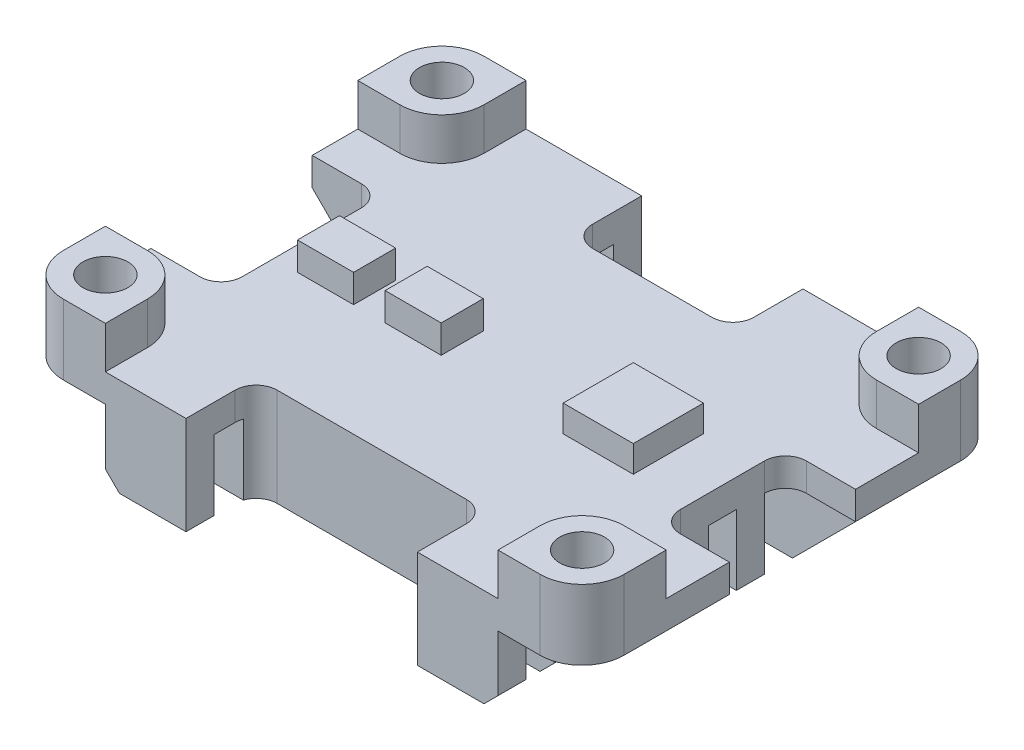
SolidWorks part; units mm, degrees
material "1060 Сплав"
ref_plane "Спереди" through (0, 0, 0) normal (0, 0, 1) x (1, 0, 0)
ref_plane "Сверху" through (0, 0, 0) normal (0, 1, 0) x (1, 0, 0)
ref_plane "Справа" through (0, 0, 0) normal (1, 0, 0) x (0, 0, -1)
other "Configuration Table"
sketch "Эскиз1" plane through (0, 0, 0) normal (0, 1, 0) x (1, 0, 0)
  line L1 (-17, 15) -> (17, 15)
  line L2 (-20, 12) -> (-20, -12)
  line L3 (-17, -15) -> (17, -15)
  line L4 (20, 12) -> (20, -12)
  line L5 (-20, 15) -> (20, -15) construction
  line L6 (-20, -15) -> (20, 15) construction
  line L7 (-17, -12) -> (17, -12) construction
  line L8 (-17, -12) -> (-17, 12) construction
  line L9 (-17, 12) -> (17, 12) construction
  line L10 (17, -12) -> (17, 12) construction
  line L11 (-17, -12) -> (17, 12) construction
  line L12 (-17, 12) -> (17, -12) construction
  arc A0 (-20, -12) -> (-17, -15) centre (-17, -12) ccw
  arc A1 (17, -15) -> (20, -12) centre (17, -12) ccw
  arc A2 (17, 15) -> (20, 12) centre (17, 12) cw
  arc A3 (-17, 15) -> (-20, 12) centre (-17, 12) ccw
  circle A4 centre (-17, 12) radius 1.6
  circle A5 centre (17, 12) radius 1.6
  circle A6 centre (17, -12) radius 1.6
  circle A7 centre (-17, -12) radius 1.6
  point P0 (0, 0)
  point P18 (0, 0)
  dimension "D3" = 3
  dimension "D6" = 3.2
  dimension "D7" = 3.2
  dimension "D8" = 3.2
  dimension "D9" = 3.2
  dimension "D1" = 40
  dimension "D2" = 30
  dimension "D4" = 3
  dimension "D5" = 3
extrude "Бобышка-Вытянуть1" add sketch "Эскиз1" along normal blind 7
sketch "Эскиз2" plane through (0, 7, 0) normal (0, 1, 0) x (1, 0, 0)
  line L0 (-17, 9) -> (-20, 9)
  line L1 (-20, 12) -> (-20, -12) construction
  line L2 (-20, 9) -> (-20, 12)
  line L3 (-14, 12) -> (-14, 15)
  line L4 (17, 15) -> (-17, 15) construction
  line L5 (-14, 15) -> (-17, 15)
  line L6 (14, 12) -> (14, 15)
  line L7 (14, 15) -> (17, 15)
  line L8 (17, 9) -> (20, 9)
  line L9 (20, -12) -> (20, 12) construction
  line L10 (20, 9) -> (20, 12)
  line L11 (17, -9) -> (20, -9)
  line L12 (20, -9) -> (20, -12)
  line L13 (17, -15) -> (14, -15)
  line L14 (-17, -15) -> (17, -15) construction
  line L15 (14, -15) -> (14, -12)
  line L16 (-17, -9) -> (-20, -9)
  line L17 (-20, -9) -> (-20, -12)
  line L18 (-17, -15) -> (-14, -15)
  line L19 (-14, -15) -> (-14, -12)
  line L21 (6.15, 2.5) -> (11.15, 2.5)
  line L22 (6.15, 2.5) -> (6.15, -2.5)
  line L23 (6.15, -2.5) -> (11.15, -2.5)
  line L24 (11.15, 2.5) -> (11.15, -2.5)
  line L25 (6.15, 2.5) -> (11.15, -2.5) construction
  line L26 (6.15, -2.5) -> (11.15, 2.5) construction
  line L27 (-7.05, 1) -> (-3.05, 1)
  line L28 (-7.05, 1) -> (-7.05, -2)
  line L29 (-7.05, -2) -> (-3.05, -2)
  line L30 (-3.05, 1) -> (-3.05, -2)
  line L31 (-7.05, 1) -> (-3.05, -2) construction
  line L32 (-7.05, -2) -> (-3.05, 1) construction
  line L33 (-13.3, 1) -> (-9.3, 1)
  line L34 (-13.3, 1) -> (-13.3, -2)
  line L35 (-13.3, -2) -> (-9.3, -2)
  line L36 (-9.3, 1) -> (-9.3, -2)
  line L37 (-13.3, 1) -> (-9.3, -2) construction
  line L38 (-13.3, -2) -> (-9.3, 1) construction
  circle A0 centre (-17, 12) radius 1.6
  arc A1 (-17, 15) -> (-20, 12) centre (-17, 12) ccw
  circle A2 centre (17, 12) radius 1.6
  arc A3 (14, 12) -> (17, 9) centre (17, 12) ccw
  circle A4 centre (17, -12) radius 1.6
  arc A5 (17, -9) -> (14, -12) centre (17, -12) ccw
  circle A6 centre (-17, -12) radius 1.6
  arc A7 (-20, -12) -> (-17, -15) centre (-17, -12) ccw
  arc A8 (17, -15) -> (20, -12) centre (17, -12) ccw construction
  arc A9 (20, 12) -> (17, 15) centre (17, 12) ccw construction
  arc A10 (-17, 15) -> (-20, 12) centre (-17, 12) ccw construction
  circle A11 centre (-17, 12) radius 1.6 construction
  circle A12 centre (17, 12) radius 1.6 construction
  circle A13 centre (17, -12) radius 1.6 construction
  circle A14 centre (-17, -12) radius 1.6 construction
  arc A15 (-17, 9) -> (-14, 12) centre (-17, 12) ccw
  arc A16 (20, 12) -> (17, 15) centre (17, 12) ccw
  arc A17 (17, -15) -> (20, -12) centre (17, -12) ccw
  arc A18 (-14, -12) -> (-17, -9) centre (-17, -12) ccw
  point P3 (8.65, 0)
  point P67 (-5.05, -0.5)
  point P72 (-11.3, -0.5)
  point P77 (-6.0572, -1.681)
  point P78 (-12.49, -2.3596)
  dimension "D1" = 5
  dimension "D2" = 8.85
  dimension "D3" = 12.5
  dimension "D4" = 4
  dimension "D5" = 3
  dimension "D6" = 6.25
  dimension "D7" = 14
  dimension "D8" = 6.7
extrude "Бобышка-Вытянуть2" add sketch "Эскиз2" along normal blind 3
ref_plane "Плоскость1" through (0, 5, 0) normal (0, 1, 0) x (1, 0, 0)
sketch "Эскиз4" plane through (0, 0, 0) normal (0, -1, 0) x (1, 0, 0)
  line L0 (17, -15) -> (-17, -15) construction
  line L1 (-5.75, -20) -> (5.75, -20)
  line L2 (-5.75, -20) -> (-5.75, -11.5)
  line L3 (-4.25, -10) -> (4.25, -10)
  line L4 (5.75, -20) -> (5.75, -11.5)
  line L5 (-5.75, -20) -> (5.75, -10) construction
  line L6 (-5.75, -10) -> (5.75, -20) construction
  line L7 (-20, -12) -> (-20, 12) construction
  line L8 (-25, 5.75) -> (-16.5, 5.75)
  line L9 (-25, 5.75) -> (-25, -5.75)
  line L10 (-25, -5.75) -> (-16.5, -5.75)
  line L11 (-15, 4.25) -> (-15, -4.25)
  line L12 (-25, 5.75) -> (-15, -5.75) construction
  line L13 (-25, -5.75) -> (-15, 5.75) construction
  line L14 (-17, 15) -> (17, 15) construction
  line L15 (-8.25, 20) -> (8.25, 20)
  line L16 (-8.25, 20) -> (-8.25, 11.5)
  line L17 (-6.75, 10) -> (6.75, 10)
  line L18 (8.25, 20) -> (8.25, 11.5)
  line L19 (-8.25, 20) -> (8.25, 10) construction
  line L20 (-8.25, 10) -> (8.25, 20) construction
  line L21 (20, 12) -> (20, -12) construction
  line L22 (25, 4.5) -> (16.5, 4.5)
  line L23 (25, 4.5) -> (25, -4.5)
  line L24 (25, -4.5) -> (16.5, -4.5)
  line L25 (15, 3) -> (15, -3)
  line L26 (25, 4.5) -> (15, -4.5) construction
  line L27 (25, -4.5) -> (15, 4.5) construction
  arc A0 (-5.75, -11.5) -> (-4.25, -10) centre (-4.25, -11.5) cw
  arc A1 (4.25, -10) -> (5.75, -11.5) centre (4.25, -11.5) cw
  arc A2 (-16.5, -5.75) -> (-15, -4.25) centre (-16.5, -4.25) ccw
  arc A3 (-16.5, 5.75) -> (-15, 4.25) centre (-16.5, 4.25) cw
  arc A4 (16.5, -4.5) -> (15, -3) centre (16.5, -3) cw
  arc A5 (16.5, 4.5) -> (15, 3) centre (16.5, 3) ccw
  arc A6 (-8.25, 11.5) -> (-6.75, 10) centre (-6.75, 11.5) ccw
  arc A7 (6.75, 10) -> (8.25, 11.5) centre (6.75, 11.5) ccw
  point P0 (0, -15)
  point P13 (-20, 0)
  point P20 (0, 15)
  point P27 (20, 0)
  dimension "D3" = 1.5
  dimension "D6" = 1.5
  dimension "D9" = 1.5
  dimension "D10" = 1.5
  dimension "D1" = 11.5
  dimension "D2" = 5
  dimension "D4" = 11.5
  dimension "D5" = 5
  dimension "D7" = 9
  dimension "D8" = 5
  dimension "D11" = 5
  dimension "D12" = 16.5
extrude "Вырез-Вытянуть1" cut sketch "Эскиз4" against normal blind 31
sketch "Эскиз5" plane through (0, 0, 0) normal (0, -1, 0) x (1, 0, 0)
  line L0 (-27.2414, 5) -> (-27.2414, 3)
  line L1 (-27.2414, 1) -> (27.2414, 1)
  line L2 (-27.2414, 1) -> (-27.2414, -1)
  line L3 (-27.2414, -1) -> (27.2414, -1)
  line L4 (27.2414, 1) -> (27.2414, -1)
  line L5 (-27.2414, 1) -> (27.2414, -1) construction
  line L6 (-27.2414, -1) -> (27.2414, 1) construction
  line L7 (-27.2414, 5) -> (27.2414, 5)
  line L8 (27.2414, 5) -> (27.2414, 3)
  line L9 (-27.2414, 3) -> (27.2414, 3)
  line L10 (-27.2414, 9) -> (-27.2414, 7)
  line L11 (-27.2414, 9) -> (27.2414, 9)
  line L12 (27.2414, 9) -> (27.2414, 7)
  line L13 (-27.2414, 7) -> (27.2414, 7)
  line L14 (-125.5108, 0) -> (125.5108, 0) construction
  line L15 (-125.5108, 60.0787) -> (125.5108, 60.0787)
  line L16 (-125.5108, 60.0787) -> (-125.5108, -60.0787)
  line L17 (-125.5108, -60.0787) -> (125.5108, -60.0787)
  line L18 (125.5108, 60.0787) -> (125.5108, -60.0787)
  line L19 (-125.5108, 60.0787) -> (125.5108, -60.0787) construction
  line L20 (-125.5108, -60.0787) -> (125.5108, 60.0787) construction
  line L21 (-27.2414, -5) -> (27.2414, -5)
  line L22 (27.2414, -5) -> (27.2414, -3)
  line L23 (-27.2414, -3) -> (27.2414, -3)
  line L24 (-27.2414, -5) -> (-27.2414, -3)
  line L25 (-27.2414, -9) -> (27.2414, -9)
  line L26 (27.2414, -9) -> (27.2414, -7)
  line L27 (-27.2414, -7) -> (27.2414, -7)
  line L28 (-27.2414, -9) -> (-27.2414, -7)
  line L29 (-27.2414, 13) -> (-27.2414, 11)
  line L30 (-27.2414, 13) -> (27.2414, 13)
  line L31 (27.2414, 13) -> (27.2414, 11)
  line L32 (-27.2414, 11) -> (27.2414, 11)
  line L34 (-27.2414, -13) -> (27.2414, -13)
  line L35 (27.2414, -13) -> (27.2414, -11)
  line L36 (-27.2414, -11) -> (27.2414, -11)
  line L37 (-27.2414, -13) -> (-27.2414, -11)
  circle A0 centre (17, 12) radius 3 construction
  arc A1 (20, 12) -> (17, 15) centre (17, 12) ccw construction
  circle A2 centre (-17, 12) radius 3 construction
  circle A3 centre (17, -12) radius 3 construction
  circle A4 centre (-17, -12) radius 3 construction
  arc A5 (17, -15) -> (20, -12) centre (17, -12) ccw construction
  point P0 (0, 0)
  point P6 (0, 0)
  line M39 (-5.75, -15) -> (-5.75, -11.5)
  arc M40 (-5.75, -11.5) -> (-4.25, -10) centre (-4.25, -11.5) cw
  arc M42 (4.25, -10) -> (5.75, -11.5) centre (4.25, -11.5) cw
  line M43 (5.75, -11.5) -> (5.75, -15)
  arc M45 (17, -15) -> (20, -12) centre (17, -12) ccw
  line M46 (20, -12) -> (20, -4.5)
  line M47 (20, -4.5) -> (16.5, -4.5)
  arc M48 (16.5, -4.5) -> (15, -3) centre (16.5, -3) cw
  line M49 (15, -3) -> (15, 3)
  arc M50 (15, 3) -> (16.5, 4.5) centre (16.5, 3) cw
  line M51 (16.5, 4.5) -> (20, 4.5)
  line M52 (20, 4.5) -> (20, 12)
  arc M53 (20, 12) -> (17, 15) centre (17, 12) ccw
  line M55 (8.25, 15) -> (8.25, 11.5)
  arc M56 (8.25, 11.5) -> (6.75, 10) centre (6.75, 11.5) cw
  arc M58 (-6.75, 10) -> (-8.25, 11.5) centre (-6.75, 11.5) cw
  line M59 (-8.25, 11.5) -> (-8.25, 15)
  arc M61 (-17, 15) -> (-20, 12) centre (-17, 12) ccw
  line M62 (-20, 12) -> (-20, 5.75)
  arc M64 (-16.5, 5.75) -> (-15, 4.25) centre (-16.5, 4.25) cw
  line M65 (-15, 4.25) -> (-15, -4.25)
  arc M66 (-15, -4.25) -> (-16.5, -5.75) centre (-16.5, -4.25) cw
  line M68 (-20, -5.75) -> (-20, -12)
  arc M69 (-20, -12) -> (-17, -15) centre (-17, -12) ccw
  circle M70 centre (-17, -12) radius 1.6
  circle M71 centre (17, -12) radius 1.6
  circle M72 centre (17, 12) radius 1.6
  circle M73 centre (-17, 12) radius 1.6
  dimension "D1" = 2
  dimension "D2" = 4
  dimension "D3" = 2
extrude "Вырез-Вытянуть2" cut sketch "Эскиз5" against normal up to surface (5 mm away) contours L36 L34 M70 M39 M40 | L36 L34 M42 M43 M71 | L36 L34 M71 M45 M46 | L36 L34 M68 M69 M70 | L27 L25 M68 M46 | L23 L21 M65 M66 M46 M47 M48 | L3 L1 M65 M49 | L9 L7 M65 M50 M51 M52 M64 | L13 L11 M62 M52 | L32 L30 M73 M58 M59 | L32 L30 M62 M73 M61 | L32 L30 M56 M72 M55 | L32 L30 M72 M52 M53
sketch "Эскиз6" plane through (0, 5, 0) normal (0, 1, 0) x (1, 0, 0)
  line L0 (14, 12) -> (14, 9)
  line L1 (14, 9) -> (17, 9)
  line L2 (14, -12) -> (14, -9)
  line L3 (14, -9) -> (17, -9)
  line L4 (-20, 9) -> (-17, 9)
  line L5 (-20, 12) -> (-20, 9)
  line L6 (-14, 15) -> (-17, 15)
  line L7 (-14, 12) -> (-14, 15)
  line L8 (-20, 9) -> (-17, 9)
  line L9 (-20, 12) -> (-20, 9)
  line L10 (-14, 15) -> (-17, 15)
  line L11 (-14, 12) -> (-14, 15)
  line L12 (20, -9) -> (17, -9)
  line L13 (20, -12) -> (20, -9)
  line L14 (14, -15) -> (17, -15)
  line L15 (14, -12) -> (14, -15)
  line L16 (20, -9) -> (17, -9)
  line L17 (20, -12) -> (20, -9)
  line L18 (14, -15) -> (17, -15)
  line L19 (14, -12) -> (14, -15)
  line L20 (20, 9) -> (20, 12)
  line L21 (17, 15) -> (14, 15)
  line L22 (14, 15) -> (14, 12)
  line L23 (17, 9) -> (20, 9)
  line L24 (20, 9) -> (20, 12)
  line L25 (17, 15) -> (14, 15)
  line L26 (14, 15) -> (14, 12)
  line L27 (17, 9) -> (20, 9)
  line L52 (-14, -15) -> (-14, -12)
  line L53 (-17, -9) -> (-20, -9)
  line L54 (-20, -9) -> (-20, -12)
  line L55 (-17, -15) -> (-14, -15)
  line L56 (-14, -15) -> (-14, -12)
  line L57 (-17, -9) -> (-20, -9)
  line L58 (-20, -9) -> (-20, -12)
  line L59 (-17, -15) -> (-14, -15)
  line L60 (-17, -9) -> (-14, -9)
  line L61 (-14, -9) -> (-14, -12)
  line L62 (-14, 12) -> (-14, 9)
  line L63 (-14, 9) -> (-17, 9)
  circle A1 centre (-17, -12) radius 1.6
  circle A2 centre (-17, -12) radius 1.6
  circle A3 centre (17, -12) radius 1.6
  circle A4 centre (17, -12) radius 1.6
  circle A5 centre (17, 12) radius 1.6
  circle A6 centre (17, 12) radius 1.6
  circle A7 centre (-17, 12) radius 1.6
  circle A8 centre (-17, 12) radius 1.6
  arc A10 (-17, 15) -> (-20, 12) centre (-17, 12) ccw
  arc A11 (-17, 9) -> (-14, 12) centre (-17, 12) ccw
  arc A12 (-17, 15) -> (-20, 12) centre (-17, 12) ccw
  arc A14 (17, -15) -> (20, -12) centre (17, -12) ccw
  arc A15 (17, -9) -> (14, -12) centre (17, -12) ccw
  arc A16 (17, -15) -> (20, -12) centre (17, -12) ccw
  arc A18 (20, 12) -> (17, 15) centre (17, 12) ccw
  arc A19 (14, 12) -> (17, 9) centre (17, 12) ccw
  arc A20 (20, 12) -> (17, 15) centre (17, 12) ccw
  arc A22 (-14, -12) -> (-17, -9) centre (-17, -12) ccw
  arc A23 (-20, -12) -> (-17, -15) centre (-17, -12) ccw
  arc A25 (-20, -12) -> (-17, -15) centre (-17, -12) ccw
  dimension "D1" = 0
  dimension "D2" = 0
  dimension "D3" = 0
  dimension "D4" = 0
  dimension "D5" = 0
  dimension "D6" = 0
  dimension "D7" = 0
  dimension "D11" = 0
extrude "Вырез-Вытянуть3" cut sketch "Эскиз6" against normal blind 31
chamfer "Фаска1" distance 5 angle 45 2 edges at (20, 0, 6) (20, 0, -6)
chamfer "Фаска2" distance 5 angle 45 1 edges at (-20, 0, 6.375)
chamfer "Фаска3" distance 1 angle 45 8 edges at (-14, 0, -14) (-14, 0, -10) (-14, 0, 14) (-14, 0, 10) (14, 0, 10) (14, 0, 14) (14, 0, -14) (14, 0, -10)
sketch "Эскиз7" plane through (0, 10, 0) normal (0, 1, 0) x (1, 0, 0)
  line L1 (3.7844, 4.9963) -> (13.6781, 4.9963)
  line L2 (3.7844, 4.9963) -> (3.7844, -4.9963)
  line L3 (3.7844, -4.9963) -> (13.6781, -4.9963)
  line L4 (13.6781, 4.9963) -> (13.6781, -4.9963)
  line L5 (3.7844, 4.9963) -> (13.6781, -4.9963) construction
  line L6 (3.7844, -4.9963) -> (13.6781, 4.9963) construction
  point P0 (8.7312, 0)
extrude "Вырез-Вытянуть4" cut sketch "Эскиз7" against normal blind 1.1
sketch "Эскиз8" plane through (0, 10, 0) normal (0, 1, 0) x (1, 0, 0)
  line L1 (-17.5862, 3.1165) -> (2.1024, 3.1165)
  line L2 (-17.5862, 3.1165) -> (-17.5862, -4.3038)
  line L3 (-17.5862, -4.3038) -> (2.1024, -4.3038)
  line L4 (2.1024, 3.1165) -> (2.1024, -4.3038)
  line L5 (-17.5862, 3.1165) -> (2.1024, -4.3038) construction
  line L6 (-17.5862, -4.3038) -> (2.1024, 3.1165) construction
  point P0 (-7.7419, -0.5936)
extrude "Вырез-Вытянуть5" cut sketch "Эскиз8" against normal blind 1
